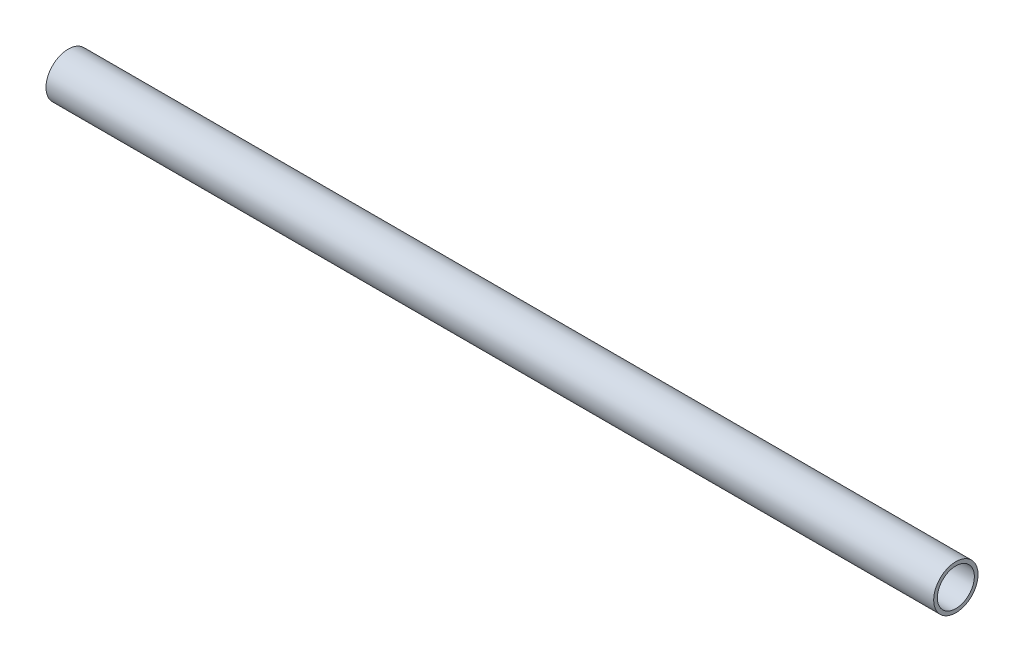
SolidWorks part; units mm, degrees
ref_plane "Ebene vorne" through (0, 0, 0) normal (0, 0, 1) x (1, 0, 0)
ref_plane "Ebene oben" through (0, 0, 0) normal (0, 1, 0) x (1, 0, 0)
ref_plane "Ebene rechts" through (0, 0, 0) normal (1, 0, 0) x (0, 0, -1)
sketch "Sketch1" plane through (0, 0, 0) normal (0, 1, 0) x (1, 0, 0)
  line L0 (-0.9565, 0) -> (27.6627, 0) construction
  line L2 (0, 3) -> (120, 3)
  line L3 (0, 3) -> (0, 2.5)
  line L4 (0, 2.5) -> (120, 2.5)
  line L5 (120, 3) -> (120, 2.5)
  dimension "D1" = 6
  dimension "D2" = 5
  dimension "D3" = 120
revolve "Revolve1" add sketch "Sketch1" angle 360 about L0
